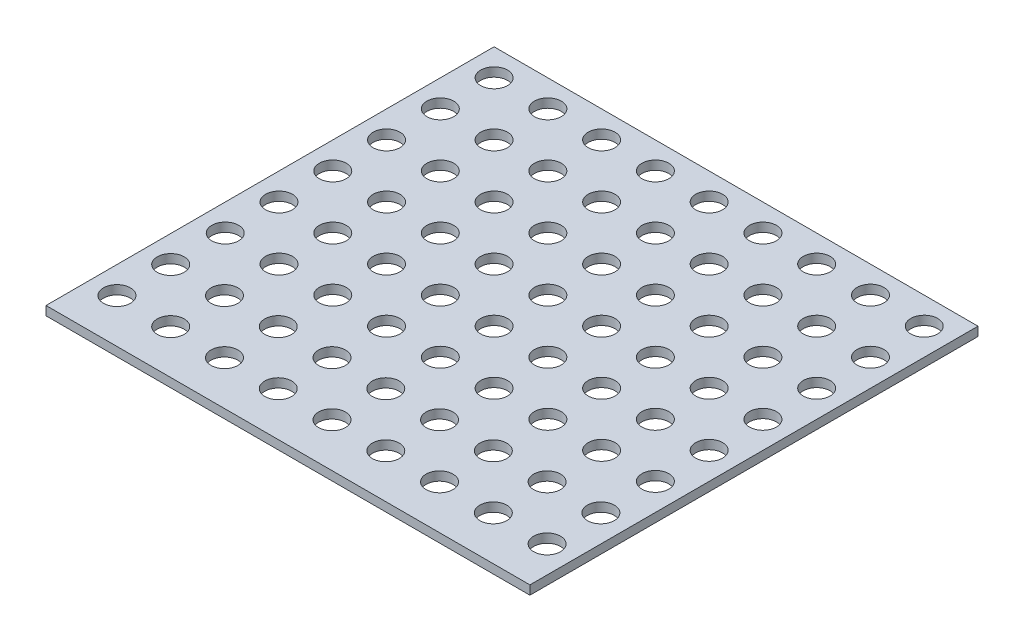
SolidWorks part; units mm, degrees
material "A286 Iron Base Superalloy"
ref_plane "Front Plane" through (0, 0, 0) normal (0, 0, 1) x (1, 0, 0)
ref_plane "Top Plane" through (0, 0, 0) normal (0, 1, 0) x (1, 0, 0)
ref_plane "Right Plane" through (0, 0, 0) normal (1, 0, 0) x (0, 0, -1)
sketch "Sketch1" plane through (0, 0, 0) normal (0, 1, 0) x (1, 0, 0)
  line L0 (0, 250) -> (15, 250)
  line L1 (0, 0) -> (270, 0)
  line L2 (0, 0) -> (0, 250)
  line L3 (0, 250) -> (270, 250)
  line L4 (270, 0) -> (270, 250)
  line L5 (15, 250) -> (15, 0) construction
  line L6 (0, 235) -> (15, 235) construction
  line L7 (0, 205) -> (15, 205) construction
  line L8 (0, 175) -> (15, 175) construction
  line L9 (0, 145) -> (15, 145) construction
  line L10 (0, 115) -> (15, 115) construction
  line L11 (0, 85) -> (15, 85) construction
  line L12 (0, 55) -> (15, 55) construction
  line L13 (0, 25) -> (15, 25) construction
  circle A0 centre (15, 235) radius 7.5
  circle A1 centre (45, 235) radius 7.5
  circle A2 centre (75, 235) radius 7.5
  circle A3 centre (105, 235) radius 7.5
  circle A4 centre (135, 235) radius 7.5
  circle A5 centre (165, 235) radius 7.5
  circle A6 centre (195, 235) radius 7.5
  circle A7 centre (225, 235) radius 7.5
  circle A8 centre (255, 235) radius 7.5
  circle A10 centre (15, 205) radius 7.5
  circle A11 centre (45, 205) radius 7.5
  circle A12 centre (75, 205) radius 7.5
  circle A13 centre (105, 205) radius 7.5
  circle A14 centre (135, 205) radius 7.5
  circle A15 centre (165, 205) radius 7.5
  circle A16 centre (195, 205) radius 7.5
  circle A17 centre (225, 205) radius 7.5
  circle A18 centre (255, 205) radius 7.5
  circle A20 centre (45, 175) radius 7.5
  circle A22 centre (165, 175) radius 7.5
  circle A23 centre (225, 175) radius 7.5
  circle A24 centre (75, 175) radius 7.5
  circle A25 centre (15, 175) radius 7.5
  circle A26 centre (135, 175) radius 7.5
  circle A27 centre (195, 175) radius 7.5
  circle A28 centre (255, 175) radius 7.5
  circle A29 centre (105, 175) radius 7.5
  circle A30 centre (105, 85) radius 7.5
  circle A31 centre (45, 145) radius 7.5
  circle A32 centre (165, 115) radius 7.5
  circle A33 centre (165, 145) radius 7.5
  circle A34 centre (225, 85) radius 7.5
  circle A35 centre (255, 85) radius 7.5
  circle A36 centre (195, 145) radius 7.5
  circle A37 centre (255, 115) radius 7.5
  circle A38 centre (45, 85) radius 7.5
  circle A39 centre (105, 115) radius 7.5
  circle A40 centre (75, 145) radius 7.5
  circle A41 centre (225, 145) radius 7.5
  circle A42 centre (75, 115) radius 7.5
  circle A43 centre (15, 85) radius 7.5
  circle A45 centre (105, 145) radius 7.5
  circle A46 centre (255, 145) radius 7.5
  circle A47 centre (45, 115) radius 7.5
  circle A48 centre (135, 115) radius 7.5
  circle A49 centre (15, 145) radius 7.5
  circle A51 centre (135, 145) radius 7.5
  circle A52 centre (165, 85) radius 7.5
  circle A53 centre (195, 85) radius 7.5
  circle A54 centre (15, 115) radius 7.5
  circle A55 centre (195, 115) radius 7.5
  circle A57 centre (225, 115) radius 7.5
  circle A58 centre (75, 85) radius 7.5
  circle A59 centre (135, 85) radius 7.5
  circle A60 centre (225, 24.5756) radius 7.5
  circle A61 centre (75, 54.5756) radius 7.5
  circle A62 centre (195, 54.5756) radius 7.5
  circle A63 centre (165, 54.5756) radius 7.5
  circle A64 centre (255, 24.5756) radius 7.5
  circle A65 centre (225, 54.5756) radius 7.5
  circle A66 centre (45, 54.5756) radius 7.5
  circle A67 centre (15, 24.5756) radius 7.5
  circle A68 centre (135, 54.5756) radius 7.5
  circle A69 centre (165, 24.5756) radius 7.5
  circle A70 centre (45, 24.5756) radius 7.5
  circle A71 centre (75, 24.5756) radius 7.5
  circle A72 centre (255, 54.5756) radius 7.5
  circle A73 centre (195, 24.5756) radius 7.5
  circle A74 centre (15, 54.5756) radius 7.5
  circle A75 centre (105, 54.5756) radius 7.5
  circle A76 centre (105, 24.5756) radius 7.5
  circle A77 centre (135, 24.5756) radius 7.5
  circle A80 centre (285, 235) radius 7.5 [skipped]
  circle A81 centre (285, 205) radius 7.5 [skipped]
  dimension "D5" = 15
  dimension "D14" = 10
  dimension "D1" = 270
  dimension "D2" = 250
  dimension "D3" = 15
  dimension "D7" = 30
  dimension "D15" = 45
  dimension "D16" = 24.5756
  dimension "D17" = 54.5756
  dimension "D4" = 15
  dimension "D8" = 30
  dimension "D9" = 30
  dimension "D10" = 30
  dimension "D11" = 30
  dimension "D12" = 30
  dimension "D13" = 30
  dimension "D6" = 10
extrude "Boss-Extrude1" add sketch "Sketch1" along normal blind 5
